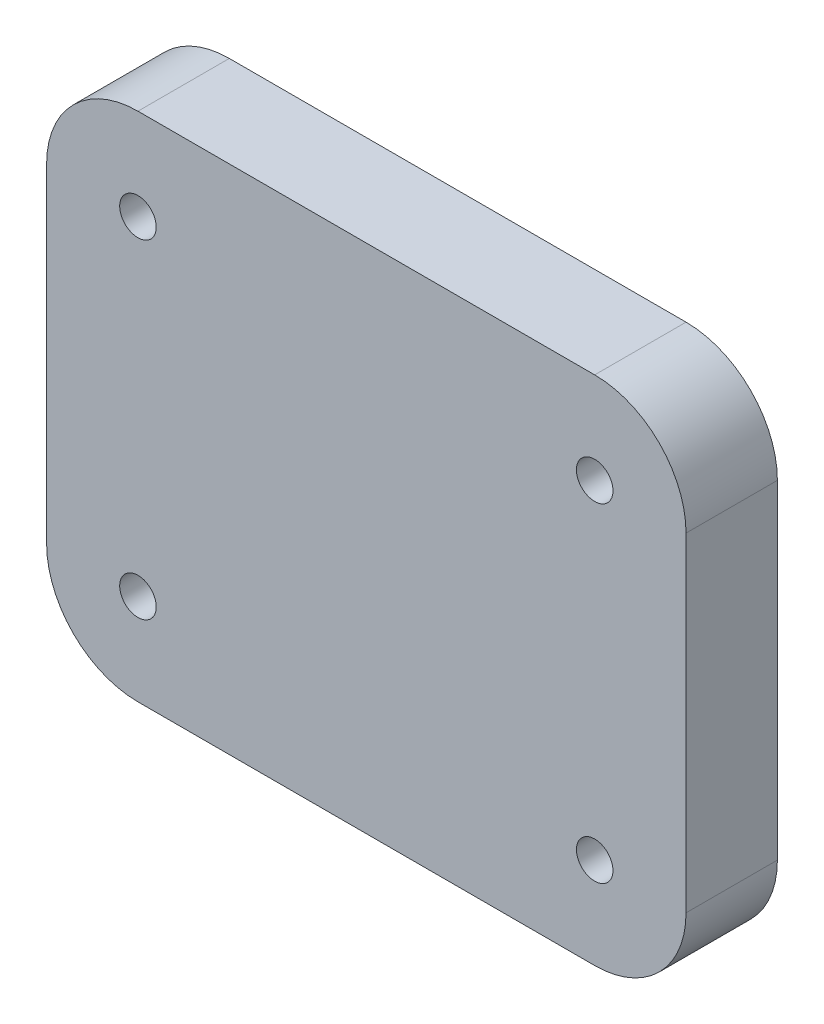
SolidWorks part; units mm, degrees
ref_plane "Front Plane" through (0, 0, 0) normal (0, 0, 1) x (1, 0, 0)
ref_plane "Top Plane" through (0, 0, 0) normal (0, 1, 0) x (1, 0, 0)
ref_plane "Right Plane" through (0, 0, 0) normal (1, 0, 0) x (0, 0, -1)
sketch "Sketch1" plane through (0, 0, 0) normal (0, 0, 1) x (1, 0, 0)
  line L0 (-17.5, 14) -> (-17.5, -14)
  line L2 (17.5, 14) -> (-17.5, 14)
  line L3 (-17.5, -14) -> (17.5, -14)
  line L4 (17.5, -14) -> (17.5, 14)
extrude "Boss-Extrude1" add sketch "Sketch1" along normal blind 5
fillet "Fillet1" radius 5 4 edges at (-17.5, -14, 2.5) (-17.5, 14, 2.5) (17.5, -14, 2.5) (17.5, 14, 2.5)
sketch "Sketch2" plane through (0, 0, 5) normal (0, 0, 1) x (1, 0, 0)
  circle A0 centre (-12.5, -9) radius 1
  circle A1 centre (-12.5, 9) radius 1
  circle A2 centre (12.5, 9) radius 1
  circle A3 centre (12.5, -9) radius 1
extrude "Cut-Extrude1" cut sketch "Sketch2" against normal through all contours A0 | A1 | A2 | A3
